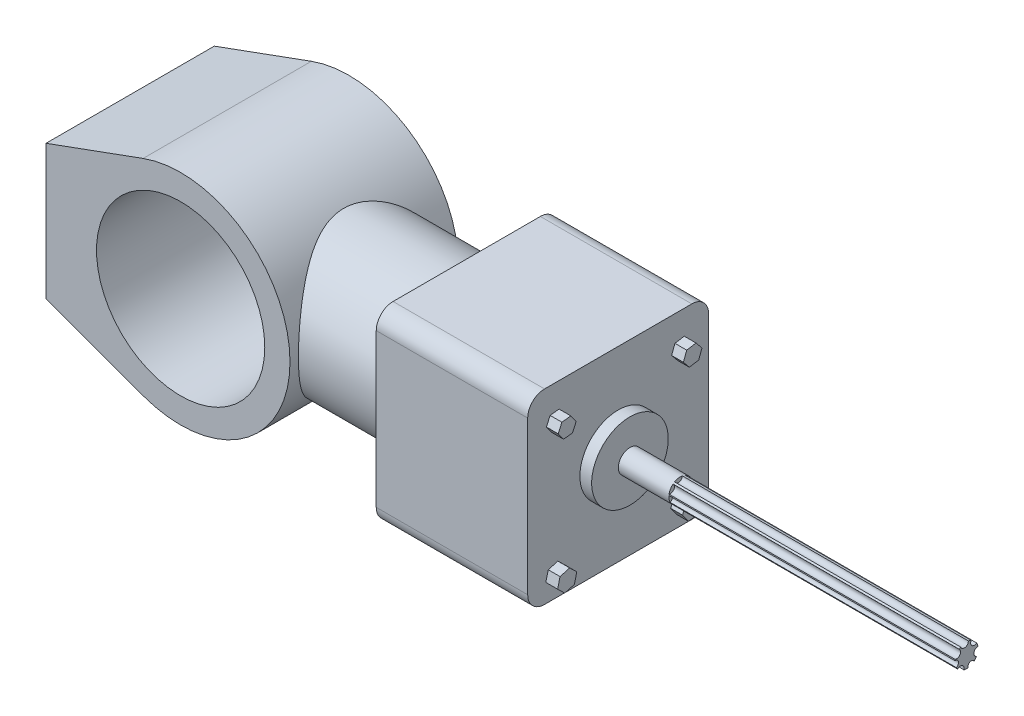
SolidWorks part; units mm, degrees
ref_plane "Ön Düzlem" through (0, 0, 0) normal (0, 0, 1) x (1, 0, 0)
ref_plane "Üst Düzlem" through (0, 0, 0) normal (0, 1, 0) x (1, 0, 0)
ref_plane "Sağ Düzlem" through (0, 0, 0) normal (1, 0, 0) x (0, 0, -1)
sketch "Çizim1" plane through (0, 0, 0) normal (0, 0, 1) x (1, 0, 0)
  line L0 (-80, -40) -> (-80, 40)
  line L1 (-80, 40) -> (-22.2817, 61.0617)
  line L2 (-80, -40) -> (-22.2817, -61.0617)
  arc A0 (-22.2817, -61.0617) -> (-22.2817, 61.0617) centre (0, 0) ccw
  circle A1 centre (0, 0) radius 50
  point P7 (-80, 0)
  dimension "D1" = 130
  dimension "D2" = 100
  dimension "D3" = 80
  dimension "D4" = 80
extrude "Yükseklik-Ekstrüzyon1" add sketch "Çizim1" along normal mid plane 100
ref_plane "Düzlem1" through (120, 0, 0) normal (1, 0, 0) x (0, 0, -1)
sketch "Çizim2" plane through (120, 0, 0) normal (1, 0, 0) x (0, 0, -1)
  circle A0 centre (0, 0) radius 45
  dimension "D1" = 90
extrude "Yükseklik-Ekstrüzyon2" add sketch "Çizim2" against normal up to next
sketch "Croquis1" plane through (120, 0, 0) normal (1, 0, 0) x (0, 0, -1)
  line L1 (-43.7608, 55.4633) -> (43.7608, 55.4633)
  line L2 (-53.7608, 45.4633) -> (-53.7608, -45.4633)
  line L3 (-43.7608, -55.4633) -> (43.7608, -55.4633)
  line L4 (53.7608, 45.4633) -> (53.7608, -45.4633)
  line L5 (-53.7608, 55.4633) -> (53.7608, -55.4633) construction
  line L6 (-53.7608, -55.4633) -> (53.7608, 55.4633) construction
  arc A0 (-53.7608, -45.4633) -> (-43.7608, -55.4633) centre (-43.7608, -45.4633) ccw
  arc A1 (43.7608, -55.4633) -> (53.7608, -45.4633) centre (43.7608, -45.4633) ccw
  arc A2 (43.7608, 55.4633) -> (53.7608, 45.4633) centre (43.7608, 45.4633) cw
  arc A3 (-43.7608, 55.4633) -> (-53.7608, 45.4633) centre (-43.7608, 45.4633) ccw
  point P1 (0, 0)
  dimension "D1" = 10
extrude "Saliente-Extruir1" add sketch "Croquis1" along normal blind 90
sketch "Croquis2" plane through (210, 0, 0) normal (1, 0, 0) x (0, 0, -1)
  circle A0 centre (0, 0) radius 22.7526
extrude "Saliente-Extruir2" add sketch "Croquis2" along normal blind 7
sketch "Croquis3" plane through (210, 0, 0) normal (1, 0, 0) x (0, 0, -1)
  line L1 (-34.1267, 31.505) -> (-31.9464, 36.4083)
  line L2 (-31.9464, 36.4083) -> (-35.1026, 40.7481)
  line L3 (-35.1026, 40.7481) -> (-40.4391, 40.1846)
  line L4 (-40.4391, 40.1846) -> (-42.6194, 35.2814)
  line L5 (-42.6194, 35.2814) -> (-39.4632, 30.9415)
  line L6 (-39.4632, 30.9415) -> (-34.1267, 31.505)
  line L7 (40.8336, 31.505) -> (42.8167, 36.75)
  line L8 (42.8167, 36.75) -> (39.2659, 41.0898)
  line L9 (39.2659, 41.0898) -> (33.7321, 40.1846)
  line L10 (33.7321, 40.1846) -> (31.7491, 34.9397)
  line L11 (31.7491, 34.9397) -> (35.2999, 30.5999)
  line L12 (35.2999, 30.5999) -> (40.8336, 31.505)
  line L13 (-33.0365, -47.0061) -> (-31.5722, -41.2573)
  line L14 (-31.5722, -41.2573) -> (-35.8185, -37.1148)
  line L15 (-35.8185, -37.1148) -> (-41.5293, -38.721)
  line L16 (-41.5293, -38.721) -> (-42.9936, -44.4697)
  line L17 (-42.9936, -44.4697) -> (-38.7473, -48.6122)
  line L18 (-38.7473, -48.6122) -> (-33.0365, -47.0061)
  line L19 (40.8336, -47.8091) -> (43.3413, -42.2613)
  line L20 (43.3413, -42.2613) -> (39.7906, -37.3157)
  line L21 (39.7906, -37.3157) -> (33.7321, -37.9179)
  line L22 (33.7321, -37.9179) -> (31.2245, -43.4657)
  line L23 (31.2245, -43.4657) -> (34.7752, -48.4114)
  line L24 (34.7752, -48.4114) -> (40.8336, -47.8091)
  circle A0 centre (-37.2829, 35.8448) radius 4.6472 construction
  circle A1 centre (37.2829, 35.8448) radius 4.8561 construction
  circle A2 centre (-37.2829, -42.8635) radius 5.1375 construction
  circle A3 centre (37.2829, -42.8635) radius 5.2726 construction
  point P0 (-37.2829, 35.8448)
  point P1 (37.2829, 35.8448)
  point P2 (37.2829, -42.8635)
  point P3 (-37.2829, -42.8635)
extrude "Saliente-Extruir4" add sketch "Croquis3" along normal blind 7
sketch "Croquis4" plane through (217, 0, 0) normal (1, 0, 0) x (0, 0, -1)
  circle A0 centre (0, 0) radius 6.9133
extrude "Saliente-Extruir5" add sketch "Croquis4" along normal blind 200
sketch "Croquis5" plane through (417, 0, 0) normal (1, 0, 0) x (0, 0, -1)
  circle A0 centre (-1.2602, 6.7974) radius 2.3632
  circle A1 centre (0, 0) radius 6.9133 construction
  circle A2 centre (2.8492, -6.2988) radius 2.0152
  circle A3 centre (6.781, -1.3456) radius 2.4657
  circle A4 centre (0, 0) radius 6.9133 construction
  circle A6 centre (4.689, 5.08) radius 2.2597
  circle A7 centre (-3.5828, -5.9124) radius 2.2259
  circle A9 centre (-6.781, -1.3456) radius 2.0254
  circle A10 centre (-5.9428, 3.5321) radius 2.3906
extrude "Cortar-Extruir1" cut sketch "Croquis5" against normal blind 170
